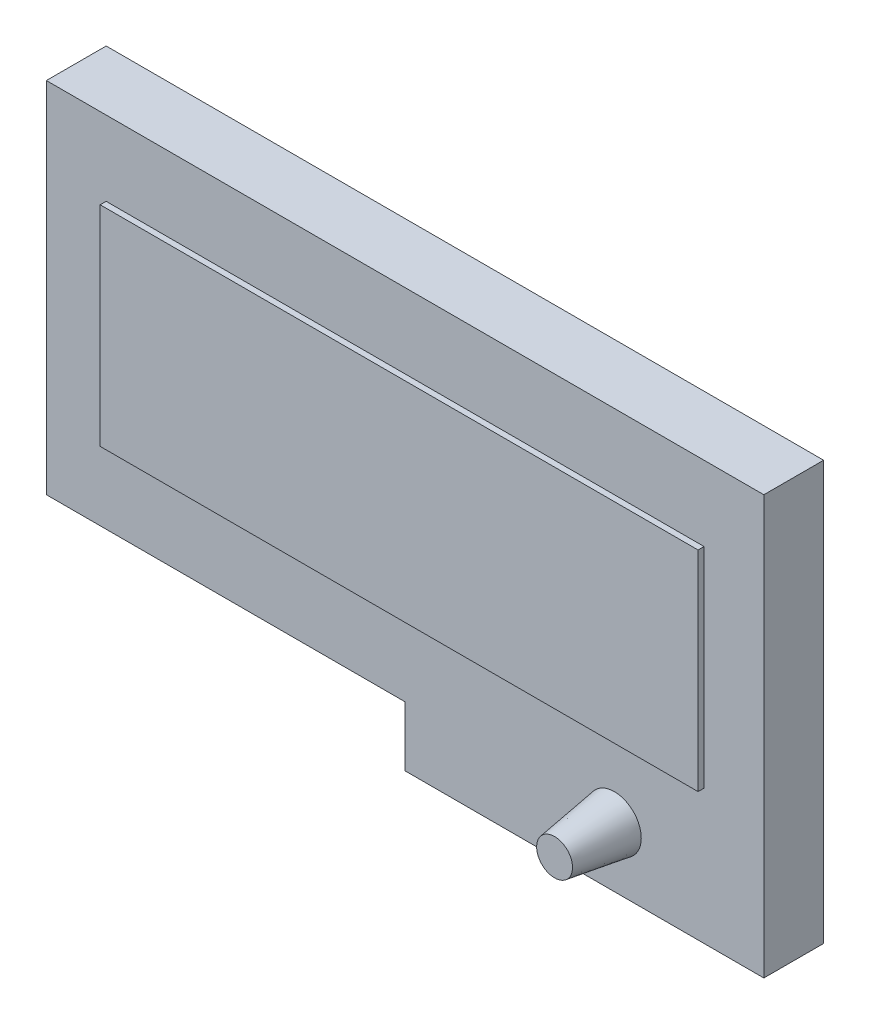
SolidWorks part; units mm, degrees
ref_plane "Piano frontale" through (0, 0, 0) normal (0, 0, 1) x (1, 0, 0)
ref_plane "Piano superiore" through (0, 0, 0) normal (0, 1, 0) x (1, 0, 0)
ref_plane "Piano destro" through (0, 0, 0) normal (1, 0, 0) x (0, 0, -1)
sketch "Schizzo1" plane through (0, 0, 0) normal (0, 0, 1) x (1, 0, 0)
  line L0 (-60, 60) -> (-60, 0)
  line L1 (-60, 0) -> (0, 0)
  line L2 (0, 0) -> (0, -10)
  line L3 (0, -10) -> (60, -10)
  line L4 (60, -10) -> (60, 0.1203)
  line L5 (60, 0.1203) -> (60, 60)
  line L6 (60, 60) -> (-60, 60)
  dimension "D1" = 10
  dimension "D2" = 70
  dimension "D3" = 120
  dimension "D4" = 60
extrude "Estrusione-Estrusione1" add sketch "Schizzo1" along normal blind 10
sketch "Schizzo2" plane through (0, 0, 10) normal (0, 0, 1) x (1, 0, 0)
  line L0 (-60, 30) -> (60, 30) construction
  line L1 (-50, 47.5) -> (50, 47.5)
  line L2 (-50, 47.5) -> (-50, 12.5)
  line L3 (-50, 12.5) -> (50, 12.5)
  line L4 (50, 47.5) -> (50, 12.5)
  line L5 (-60, 60) -> (-60, 0) construction
  line L6 (60, -10) -> (60, 60) construction
  line L7 (0, 60) -> (0, -7.8056) construction
  line L8 (60, 60) -> (-60, 60) construction
  dimension "D1" = 100
  dimension "D2" = 35
extrude "Estrusione-Estrusione2" add sketch "Schizzo2" along normal blind 1
sketch "Schizzo3" plane through (0, 0, 10) normal (0, 0, 1) x (1, 0, 0)
  line L0 (60, -10) -> (60, 60) construction
  line L1 (0, -10) -> (60, -10) construction
  circle A0 centre (35, 0) radius 4.5
  dimension "D1" = 9
  dimension "D2" = 25
  dimension "D3" = 10
ref_plane "Piano1" through (0, 0, 20) normal (0, 0, 1) x (1, 0, 0)
sketch "Schizzo4" plane through (0, 0, 20) normal (0, 0, 1) x (1, 0, 0)
  circle A0 centre (35, 0) radius 3
  dimension "D1" = 6
loft "Loft1" add profiles "Schizzo3", "Schizzo4"
